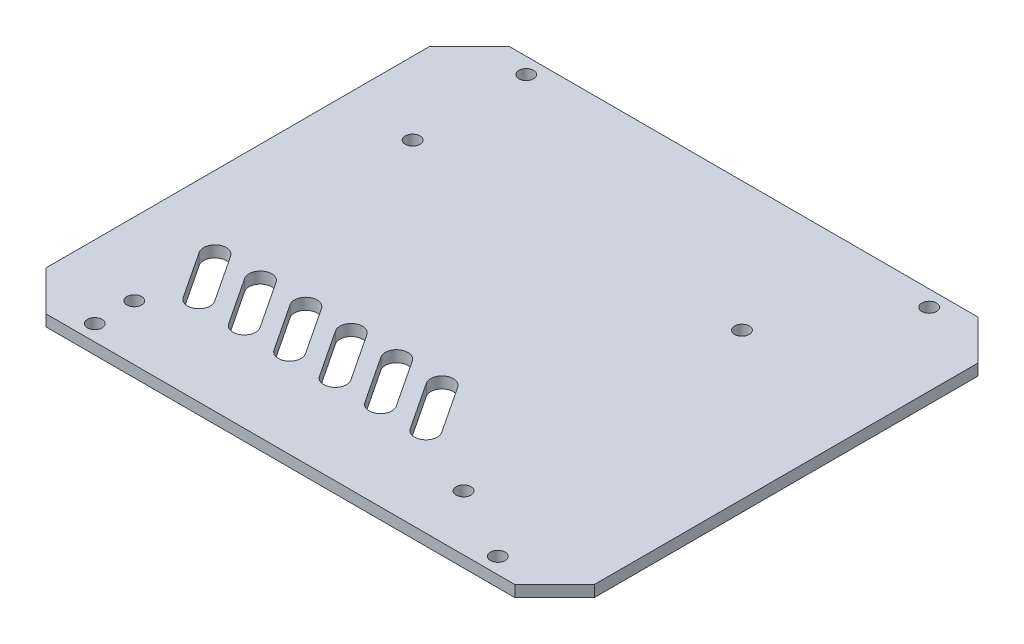
SolidWorks part; units mm, degrees
ref_plane "前视基准面" through (0, 0, 0) normal (0, 0, 1) x (1, 0, 0)
ref_plane "上视基准面" through (0, 0, 0) normal (0, 1, 0) x (1, 0, 0)
ref_plane "右视基准面" through (0, 0, 0) normal (1, 0, 0) x (0, 0, -1)
sketch "草图1" plane through (0, -19.39, 0) normal (0, -1, 0) x (1, 0, 0)
  line L16 (-51.8, -40.2958) -> (-44.7958, -47.3)
  line L17 (-44.7958, -47.3) -> (37.7958, -47.3)
  line L18 (37.7958, -47.3) -> (44.8, -40.2958)
  line L19 (44.8, -40.2958) -> (44.8, 27.2958)
  line L20 (44.8, 27.2958) -> (37.7958, 34.3)
  line L21 (-51.8, 27.2958) -> (-51.8, -40.2958)
  line L22 (37.7958, 34.3) -> (-44.7958, 34.3)
  line L23 (-44.7958, 34.3) -> (-51.8, 27.2958)
  line L24 (-51.8, -40.2958) -> (-44.7958, -47.3)
  line L25 (-44.7958, -47.3) -> (37.7958, -47.3)
  line L26 (37.7958, -47.3) -> (44.8, -40.2958)
  line L27 (44.8, -40.2958) -> (44.8, 27.2958)
  line L28 (44.8, 27.2958) -> (37.7958, 34.3)
  line L29 (-51.8, 27.2958) -> (-51.8, -40.2958)
  line L30 (37.7958, 34.3) -> (-44.7958, 34.3)
  line L31 (-44.7958, 34.3) -> (-51.8, 27.2958)
  dimension "D1" = 0.2
extrude "凸台-拉伸1" add sketch "草图1" along normal blind 2
sketch "草图2" plane through (0, -21.39, 0) normal (0, -1, 0) x (1, 0, 0)
  circle A0 centre (-39.0116, -24.5) radius 1.3
  circle A1 centre (19, -24.5) radius 1.3
  circle A2 centre (-39.0116, 24.5352) radius 1.3
  circle A3 centre (19, 24.5352) radius 1.3
  dimension "D1" = 2.6
extrude "切除-拉伸1" cut sketch "草图2" against normal up to next
sketch "草图3" plane through (0, -21.39, 0) normal (0, -1, 0) x (1, 0, 0)
  circle A0 centre (32, -44.5) radius 1.3 construction
  circle A1 centre (-39, -44.5) radius 1.3 construction
  circle A2 centre (32, 31.5) radius 1.3 construction
  circle A3 centre (-39, 31.5) radius 1.3 construction
  circle A4 centre (32, -44.5) radius 1.3
  circle A5 centre (-39, -44.5) radius 1.3
  circle A6 centre (32, 31.5) radius 1.3
  circle A7 centre (-39, 31.5) radius 1.3
extrude "切除-拉伸2" cut sketch "草图3" against normal up to next
sketch "草图4" plane through (0, -21.39, 0) normal (0, -1, 0) x (1, 0, 0)
  line L0 (-38.9928, 31.6194) -> (-39.0044, 24.6546) construction
  line L1 (-39.0282, 10.3) -> (-33.5143, 18.6425) construction
  line L2 (-40.6967, 11.4028) -> (-35.1828, 19.7453)
  line L3 (-37.3597, 9.1972) -> (-31.8458, 17.5397)
  line L5 (37.7958, 34.3) -> (-44.7958, 34.3) construction
  line L6 (-31.0282, 10.3) -> (-25.5143, 18.6425) construction
  line L9 (-32.6967, 11.4028) -> (-27.1828, 19.7453)
  line L12 (-29.3597, 9.1972) -> (-23.8458, 17.5397)
  line L15 (-23.0282, 10.3) -> (-17.5143, 18.6425) construction
  line L18 (-24.6967, 11.4028) -> (-19.1828, 19.7453)
  line L21 (-21.3597, 9.1972) -> (-15.8458, 17.5397)
  line L22 (-15.0282, 10.3) -> (-9.5143, 18.6425) construction
  line L23 (-16.6967, 11.4028) -> (-11.1828, 19.7453)
  line L24 (-13.3597, 9.1972) -> (-7.8458, 17.5397)
  line L25 (-7.0282, 10.3) -> (-1.5143, 18.6425) construction
  line L26 (-8.6967, 11.4028) -> (-3.1828, 19.7453)
  line L27 (-5.3597, 9.1972) -> (0.1542, 17.5397)
  line L28 (0.9718, 10.3) -> (6.4857, 18.6425) construction
  line L29 (-0.6967, 11.4028) -> (4.8172, 19.7453)
  line L30 (2.6403, 9.1972) -> (8.1542, 17.5397)
  arc A0 (-40.6967, 11.4028) -> (-37.3597, 9.1972) centre (-39.0282, 10.3) ccw
  arc A1 (-31.8458, 17.5397) -> (-35.1828, 19.7453) centre (-33.5143, 18.6425) ccw
  arc A12 (-32.6967, 11.4028) -> (-29.3597, 9.1972) centre (-31.0282, 10.3) ccw
  arc A13 (-23.8458, 17.5397) -> (-27.1828, 19.7453) centre (-25.5143, 18.6425) ccw
  arc A14 (-24.6967, 11.4028) -> (-21.3597, 9.1972) centre (-23.0282, 10.3) ccw
  arc A15 (-15.8458, 17.5397) -> (-19.1828, 19.7453) centre (-17.5143, 18.6425) ccw
  arc A16 (-16.6967, 11.4028) -> (-13.3597, 9.1972) centre (-15.0282, 10.3) ccw
  arc A17 (-7.8458, 17.5397) -> (-11.1828, 19.7453) centre (-9.5143, 18.6425) ccw
  arc A18 (-8.6967, 11.4028) -> (-5.3597, 9.1972) centre (-7.0282, 10.3) ccw
  arc A19 (0.1542, 17.5397) -> (-3.1828, 19.7453) centre (-1.5143, 18.6425) ccw
  arc A20 (-0.6967, 11.4028) -> (2.6403, 9.1972) centre (0.9718, 10.3) ccw
  arc A21 (8.1542, 17.5397) -> (4.8172, 19.7453) centre (6.4857, 18.6425) ccw
  point P6 (-36.2713, 14.4713)
  point P15 (-28.2713, 14.4713)
  point P22 (-20.2713, 14.4713)
  point P29 (-12.2713, 14.4713)
  point P36 (-4.2713, 14.4713)
  point P43 (3.7287, 14.4713)
  dimension "D1" = 2
  dimension "D2" = 10
  dimension "D3" = 5.5
  dimension "D4" = 12.8
  dimension "D5" = 24
  dimension "D6" = 6
extrude "切除-拉伸3" cut sketch "草图4" against normal up to next
sketch "草图5" plane through (0, -21.39, 0) normal (0, -1, 0) x (1, 0, 0)
  point P0 (-34.5006, 0.7543)
sketch_block_instance "块1-1"
sketch_block "块1"
sketch "草图6" plane through (0, -19.39, 0) normal (0, 1, 0) x (1, 0, 0)
  line L0 (-39.0322, 2.6968) -> (-34.8198, 0.2624) construction
  line L1 (-34.177, 0.2624) -> (-29.9873, 2.7014) construction
  line L2 (-29.9828, 3.2622) -> (-34.0539, 5.6966) construction
  line L3 (-29.6682, 9.5398) -> (-30.5435, 10.0367) construction
  line L4 (-30.6757, 9.9592) -> (-30.6757, 7.9487) construction
  line L5 (-30.6301, 7.8712) -> (-29.7548, 7.3788) construction
  line L6 (-29.6226, 7.4564) -> (-29.6226, 9.4623) construction
  line L7 (-33.3108, 9.1249) -> (-33.3108, 8.049) construction
  line L8 (-33.2652, 7.9715) -> (-32.8731, 7.7527) construction
  line L9 (-32.8458, 9.0109) -> (-33.2652, 9.2207) construction
  line L10 (-33.2652, 9.2207) -> (-33.2652, 10.0868) construction
  line L11 (-32.791, 9.8224) -> (-33.2652, 10.0868) construction
  line L12 (-34.3274, 7.7345) -> (-32.823, 6.8819) construction
  line L13 (-34.373, 12.0335) -> (-34.373, 7.8119) construction
  line L14 (-33.3563, 11.6095) -> (-34.2408, 12.111) construction
  line L15 (-33.3108, 10.1644) -> (-33.3108, 11.532) construction
  line L16 (-33.3108, 9.1249) -> (-33.3108, 10.1644) construction
  line L17 (-17.9609, 5.9474) -> (-18.6265, 5.6829) construction
  line L18 (-17.7011, 5.0538) -> (-17.0627, 4.2514) construction
  line L19 (-19.6477, 6.6221) -> (-18.9684, 6.9093) construction
  line L20 (-20.2085, 7.429) -> (-20.9333, 8.3134) construction
  line L21 (-10.1469, 9.1523) -> (-9.7593, 9.1523) construction
  line L22 (-5.5196, 7.1144) -> (-5.5196, 7.7664) construction
  line L23 (-26.0439, 6.3576) -> (-26.0439, 4.2651) construction
  line L24 (-26.0439, 4.2651) -> (-25.2871, 4.2651) construction
  line L25 (-25.2597, 6.3576) -> (-26.0439, 6.3576) construction
  line L26 (-26.7095, 3.7272) -> (-26.7095, 8.979) construction
  line L27 (-26.7095, 8.979) -> (-26.0439, 8.979) construction
  line L28 (-26.0439, 8.979) -> (-26.0439, 6.8956) construction
  line L29 (-26.0439, 6.8956) -> (-25.1731, 6.8956) construction
  line L30 (-25.2096, 3.7272) -> (-26.7095, 3.7272) construction
  line L31 (-33.1558, -0.189) -> (-33.8122, -0.5719) construction
  line L32 (-35.189, -0.5719) -> (-35.8455, -0.189) construction
  line L33 (-35.8455, -0.189) -> (-39.2511, 1.7759) construction
  line L34 (-39.2511, 1.7759) -> (-39.9076, 2.1543) construction
  line L35 (-40.596, 3.3442) -> (-40.596, 8.7967) construction
  line L36 (-39.9076, 9.9866) -> (-39.2511, 10.365) construction
  line L37 (-39.2511, 10.365) -> (-35.8455, 12.3299) construction
  line L38 (-35.8455, 12.3299) -> (-35.189, 12.7128) construction
  line L39 (-33.8122, 12.7128) -> (-33.1558, 12.3299) construction
  line L40 (-33.1558, 12.3299) -> (-29.7503, 10.365) construction
  line L41 (-29.7503, 10.365) -> (-29.0938, 9.9866) construction
  line L42 (-28.4054, 8.7967) -> (-28.4054, 3.3442) construction
  line L43 (-29.0938, 2.1543) -> (-29.7503, 1.7759) construction
  line L44 (-29.7503, 1.7759) -> (-33.1558, -0.189) construction
  line L45 (-5.3737, 8.5687) -> (-5.2826, 8.979) construction
  line L46 (-5.2826, 8.979) -> (-4.2431, 8.979) construction
  line L47 (-4.2431, 8.979) -> (-4.2431, 6.6631) construction
  line L48 (-7.6486, 5.3365) -> (-7.2018, 6.1753) construction
  line L49 (-5.4056, 8.5687) -> (-5.3737, 8.5687) construction
  line L50 (-8.0133, 5.8243) -> (-8.0133, 4.9034) construction
  line L51 (-8.0133, 4.9034) -> (-9.5086, 4.9034) construction
  line L52 (-11.3094, 7.3378) -> (-11.3094, 7.3652) construction
  line L53 (-11.3869, 8.8286) -> (-11.3869, 8.8651) construction
  line L54 (-9.5178, 8.1767) -> (-10.1606, 8.1767) construction
  line L55 (-8.6424, 5.8243) -> (-8.0133, 5.8243) construction
  line L56 (-13.8761, 4.9034) -> (-13.8761, 7.5749) construction
  line L57 (-15.0295, 7.2649) -> (-15.0295, 4.9034) construction
  line L58 (-15.0295, 4.9034) -> (-16.3014, 4.9034) construction
  line L59 (-16.3014, 4.9034) -> (-16.3014, 7.4245) construction
  line L60 (-13.7575, 8.4183) -> (-13.7302, 8.4183) construction
  line L61 (-13.7302, 8.4183) -> (-13.639, 8.979) construction
  line L62 (-13.639, 8.979) -> (-12.5996, 8.979) construction
  line L63 (-12.5996, 8.979) -> (-12.5996, 4.9034) construction
  line L64 (-12.5996, 4.9034) -> (-13.8761, 4.9034) construction
  line L65 (-21.7265, 8.979) -> (-21.7265, 5.0857) construction
  line L66 (-22.3785, 8.979) -> (-21.7265, 8.979) construction
  line L67 (-22.3785, 5.0857) -> (-22.3785, 8.979) construction
  line L68 (-21.7265, 5.0857) -> (-22.3785, 5.0857) construction
  line L69 (-3.4042, 8.979) -> (-2.1368, 8.979) construction
  line L70 (-2.1368, 8.979) -> (-2.1368, 6.6494) construction
  line L71 (-0.8102, 5.9838) -> (-0.596, 4.8851) construction
  line L72 (-2.2508, 5.61) -> (-2.2782, 5.61) construction
  line L73 (-2.2782, 5.61) -> (-2.3648, 4.9034) construction
  line L74 (-2.3648, 4.9034) -> (-3.4042, 4.9034) construction
  line L75 (-3.4042, 4.9034) -> (-3.4042, 8.979) construction
  line L76 (-39.0322, 2.6968) -> (-34.8198, 0.2624)
  line L77 (-34.177, 0.2624) -> (-29.9873, 2.7014)
  line L78 (-29.9828, 3.2622) -> (-34.0539, 5.6966)
  line L79 (-29.6682, 9.5398) -> (-30.5435, 10.0367)
  line L80 (-30.6757, 9.9592) -> (-30.6757, 7.9487)
  line L81 (-30.6301, 7.8712) -> (-29.7548, 7.3788)
  line L82 (-29.6226, 7.4564) -> (-29.6226, 9.4623)
  line L83 (-33.3108, 9.1249) -> (-33.3108, 8.049)
  line L84 (-33.2652, 7.9715) -> (-32.8731, 7.7527)
  line L85 (-32.8458, 9.0109) -> (-33.2652, 9.2207)
  line L86 (-33.2652, 9.2207) -> (-33.2652, 10.0868)
  line L87 (-32.791, 9.8224) -> (-33.2652, 10.0868)
  line L88 (-34.3274, 7.7345) -> (-32.823, 6.8819)
  line L89 (-34.373, 12.0335) -> (-34.373, 7.8119)
  line L90 (-33.3563, 11.6095) -> (-34.2408, 12.111)
  line L91 (-33.3108, 10.1644) -> (-33.3108, 11.532)
  line L92 (-33.3108, 9.1249) -> (-33.3108, 10.1644)
  line L93 (-17.9609, 5.9474) -> (-18.6265, 5.6829)
  line L94 (-17.7011, 5.0538) -> (-17.0627, 4.2514)
  line L95 (-19.6477, 6.6221) -> (-18.9684, 6.9093)
  line L96 (-20.2085, 7.429) -> (-20.9333, 8.3134)
  line L97 (-10.1469, 9.1523) -> (-9.7593, 9.1523)
  line L98 (-5.5196, 7.1144) -> (-5.5196, 7.7664)
  line L99 (-26.0439, 6.3576) -> (-26.0439, 4.2651)
  line L100 (-26.0439, 4.2651) -> (-25.2871, 4.2651)
  line L101 (-25.2597, 6.3576) -> (-26.0439, 6.3576)
  line L102 (-26.7095, 3.7272) -> (-26.7095, 8.979)
  line L103 (-26.7095, 8.979) -> (-26.0439, 8.979)
  line L104 (-26.0439, 8.979) -> (-26.0439, 6.8956)
  line L105 (-26.0439, 6.8956) -> (-25.1731, 6.8956)
  line L106 (-25.2096, 3.7272) -> (-26.7095, 3.7272)
  line L107 (-33.1558, -0.189) -> (-33.8122, -0.5719)
  line L108 (-35.189, -0.5719) -> (-35.8455, -0.189)
  line L109 (-35.8455, -0.189) -> (-39.2511, 1.7759)
  line L110 (-39.2511, 1.7759) -> (-39.9076, 2.1543)
  line L111 (-40.596, 3.3442) -> (-40.596, 8.7967)
  line L112 (-39.9076, 9.9866) -> (-39.2511, 10.365)
  line L113 (-39.2511, 10.365) -> (-35.8455, 12.3299)
  line L114 (-35.8455, 12.3299) -> (-35.189, 12.7128)
  line L115 (-33.8122, 12.7128) -> (-33.1558, 12.3299)
  line L116 (-33.1558, 12.3299) -> (-29.7503, 10.365)
  line L117 (-29.7503, 10.365) -> (-29.0938, 9.9866)
  line L118 (-28.4054, 8.7967) -> (-28.4054, 3.3442)
  line L119 (-29.0938, 2.1543) -> (-29.7503, 1.7759)
  line L120 (-29.7503, 1.7759) -> (-33.1558, -0.189)
  line L121 (-5.3737, 8.5687) -> (-5.2826, 8.979)
  line L122 (-5.2826, 8.979) -> (-4.2431, 8.979)
  line L123 (-4.2431, 8.979) -> (-4.2431, 6.6631)
  line L124 (-7.6486, 5.3365) -> (-7.2018, 6.1753)
  line L125 (-5.4056, 8.5687) -> (-5.3737, 8.5687)
  line L126 (-8.0133, 5.8243) -> (-8.0133, 4.9034)
  line L127 (-8.0133, 4.9034) -> (-9.5086, 4.9034)
  line L128 (-11.3094, 7.3378) -> (-11.3094, 7.3652)
  line L129 (-11.3869, 8.8286) -> (-11.3869, 8.8651)
  line L130 (-9.5178, 8.1767) -> (-10.1606, 8.1767)
  line L131 (-8.6424, 5.8243) -> (-8.0133, 5.8243)
  line L132 (-13.8761, 4.9034) -> (-13.8761, 7.5749)
  line L133 (-15.0295, 7.2649) -> (-15.0295, 4.9034)
  line L134 (-15.0295, 4.9034) -> (-16.3014, 4.9034)
  line L135 (-16.3014, 4.9034) -> (-16.3014, 7.4245)
  line L136 (-13.7575, 8.4183) -> (-13.7302, 8.4183)
  line L137 (-13.7302, 8.4183) -> (-13.639, 8.979)
  line L138 (-13.639, 8.979) -> (-12.5996, 8.979)
  line L139 (-12.5996, 8.979) -> (-12.5996, 4.9034)
  line L140 (-12.5996, 4.9034) -> (-13.8761, 4.9034)
  line L141 (-21.7265, 8.979) -> (-21.7265, 5.0857)
  line L142 (-22.3785, 8.979) -> (-21.7265, 8.979)
  line L143 (-22.3785, 5.0857) -> (-22.3785, 8.979)
  line L144 (-21.7265, 5.0857) -> (-22.3785, 5.0857)
  line L145 (-3.4042, 8.979) -> (-2.1368, 8.979)
  line L146 (-2.1368, 8.979) -> (-2.1368, 6.6494)
  line L147 (-0.8102, 5.9838) -> (-0.596, 4.8851)
  line L148 (-2.2508, 5.61) -> (-2.2782, 5.61)
  line L149 (-2.2782, 5.61) -> (-2.3648, 4.9034)
  line L150 (-2.3648, 4.9034) -> (-3.4042, 4.9034)
  line L151 (-3.4042, 4.9034) -> (-3.4042, 8.979)
  spline S0 degree 3 poles (1947.2043, 259.0221) (-2040.5975, -86.3945) (1971.5647, -86.1046) (-2015.9835, 259.8919) knots -24.014283 -24.014283 -24.014283 -24.014283 31.060476 31.060476 31.060476 31.060476 only from (-34.8198, 0.2624) to (-34.177, 0.2624) construction
  spline S1 degree 3 poles (-178.8618, 1996.4067) (-13.3017, -2002.4803) (85.7628, 2005.1657) (-277.1173, -1980.6649) knots -12.069605 -12.069605 -12.069605 -12.069605 23.053377 23.053377 23.053377 23.053377 only from (-29.9873, 2.7014) to (-29.9828, 3.2622) construction
  spline S2 degree 3 poles (-2011.9647, -280.5218) (1973.0796, 101.2598) (-2042.0834, 101.2623) (1942.99, -280.5143) knots -16.956312 -16.956312 -16.956312 -16.956312 31.955994 31.955994 31.955994 31.955994 only from (-34.0539, 5.6966) to (-34.9429, 5.6966) construction
  spline S3 degree 2 poles (1696.8938, 1005.9909) (-1772.9636, -998.1959) (1692.7429, 1003.6514) knots -19.544322 -19.544322 -19.544322 21.524182 21.524182 21.524182 only from (-34.9429, 5.6966) to (-39.0732, 3.3123) construction
  spline S4 degree 3 poles (312.9236, -1964.6822) (-255.5836, 1997.2947) (39.8207, -2001.4292) (20.6091, 2000.9771) knots -16.033039 -16.033039 -16.033039 -16.033039 19.060221 19.060221 19.060221 19.060221 only from (-39.0732, 3.3123) to (-39.0322, 2.6968) construction
  spline S5 degree 3 poles (1612.1466, 1139.1382) (-173.749, 124.6775) (-29.5451, -1.4055) (-29.5451, 6.2482) (-29.5451, 12.5795) (-131.1047, 41.0713) (891.7703, -1766.7786) knots -20.983072 -20.983072 -20.983072 -20.983072 3 3 3 23.1269 23.1269 23.1269 23.1269 only from (-30.1469, 6.0431) to (-30.1469, 7.1281) construction
  spline S6 degree 3 poles (-1593.6748, -1232.4433) (112.4759, -108.2288) (-30.7532, 14.45) (-30.7532, 6.9321) (-30.7532, 0.2328) (76.6581, -24.0346) (-1002.5668, 1752.6044) knots -22.899222 -22.899222 -22.899222 -22.899222 1 1 1 21.696321 21.696321 21.696321 21.696321 only from (-30.1469, 7.1281) to (-30.1469, 6.0431) construction
  spline S7 degree 3 poles (-1735.267, -1035.1971) (1720.3132, 981.2712) (-1822.079, -884.2768) (1795.5461, 824.5182) knots -24.864003 -24.864003 -24.864003 -24.864003 29.805716 29.805716 29.805716 29.805716 only from (-30.5435, 10.0367) to (-30.6757, 9.9592) construction
  spline S8 degree 3 poles (1803.8452, -787.8206) (-1835.1338, 879.7734) (1736.3613, -937.8925) (-1752.2845, 1025.0132) knots -52.644856 -52.644856 -52.644856 -52.644856 63.422153 63.422153 63.422153 63.422153 only from (-30.6757, 7.9487) to (-30.6301, 7.8712) construction
  spline S9 degree 3 poles (1675.9971, 1050.9308) (-1781.5786, -962.103) (1762.6814, 899.8753) (-1856.6746, -805.2277) knots -20.869425 -20.869425 -20.869425 -20.869425 33.809897 33.809897 33.809897 33.809897 only from (-29.7548, 7.3788) to (-29.6226, 7.4564) construction
  spline S10 degree 3 poles (-1017.153, 1748.416) (898.1967, -1765.8691) (-895.3334, 1815.971) (771.5167, -1822.726) knots -45.73326 -45.73326 -45.73326 -45.73326 46.535072 46.535072 46.535072 46.535072 only from (-29.6226, 9.4623) to (-29.6682, 9.5398) construction
  spline S11 degree 3 poles (1241.4728, -1544.2848) (-126.4363, -19.7603) (-21.5989, 9.5171) (-21.5989, 3.8639) (-21.5989, -3.1211) (-150.7291, 66.7677) (1747.5616, 931.244) knots -20.398043 -20.398043 -20.398043 -20.398043 3 3 3 28.967808 28.967808 28.967808 28.967808 only from (-22.0502, 4.2833) to (-22.0502, 3.44) construction
  spline S12 degree 3 poles (-1791.638, 931.233) (106.6275, 66.7672) (-22.5016, -3.1211) (-22.5016, 3.8639) (-22.5016, 9.5171) (82.3355, -19.7602) (-1285.567, -1544.2778) knots -24.967698 -24.967698 -24.967698 -24.967698 1 1 1 24.398007 24.398007 24.398007 24.398007 only from (-22.0502, 3.44) to (-22.0502, 4.2833) construction
  spline S13 degree 3 poles (953.112, -1731.5311) (-960.0271, 1783.9495) (831.3079, -1798.9714) (-833.3757, 1840.6921) knots -41.715469 -41.715469 -41.715469 -41.715469 50.515238 50.515238 50.515238 50.515238 only from (-33.3108, 8.049) to (-33.2652, 7.9715) construction
  spline S14 degree 3 poles (345.3515, -1953.7628) (-656.074, 2008.4671) (704.4049, -1945.0024) (-795.7723, 1856.1671) knots -18.836401 -18.836401 -18.836401 -18.836401 26.867419 26.867419 26.867419 26.867419 only from (-32.8731, 7.7527) to (-32.0799, 7.9031) construction
  spline S15 degree 3 poles (393.8329, 1947.428) (-1017.3565, -1766.8215) (1294.138, 1559.3727) (-1541.9229, -1298.5467) knots -37.738435 -37.738435 -37.738435 -37.738435 30.849118 30.849118 30.849118 30.849118 only from (-32.0799, 7.9031) to (-32.8458, 9.0109) construction
  spline S16 degree 3 poles (-1970.6267, 490.4514) (1900.3877, -652.3893) (-1909.3139, 822.203) (1735.9268, -921.8099) knots -2.984455 -2.984455 -2.984455 -2.984455 24.908291 24.908291 24.908291 24.908291 only from (-31.0405, 7.315) to (-32.791, 9.8224) construction
  spline S17 degree 3 poles (1301.0551, -1483.1694) (-1380.7778, 1570.3517) (1272.9624, -1585.6466) (-1251.2088, 1591.7607) knots -4.177868 -4.177868 -4.177868 -4.177868 21.267464 21.267464 21.267464 21.267464 only from (-32.823, 6.8819) to (-31.0405, 7.315) construction
  spline S18 degree 3 poles (-426.7908, -1953.0944) (416.9018, 1960.3516) (-543.6183, -1930.3492) (531.9657, 1925.7159) knots -40.574336 -40.574336 -40.574336 -40.574336 54.224541 54.224541 54.224541 54.224541 only from (-34.373, 7.8119) to (-34.3274, 7.7345) construction
  spline S19 degree 3 poles (-1739.7201, -1031.8845) (1717.3311, 982.0362) (-1826.4475, -880.8273) (1792.473, 825.1567) knots -21.867988 -21.867988 -21.867988 -21.867988 32.80886 32.80886 32.80886 32.80886 only from (-34.2408, 12.111) to (-34.373, 12.0335) construction
  spline S20 degree 3 poles (1326.5597, 1477.8337) (-1443.7748, -1422.5109) (1417.5131, 1403.8248) (-1515.2659, -1331.1895) knots -66.611259 -66.611259 -66.611259 -66.611259 68.63044 68.63044 68.63044 68.63044 only from (-33.3108, 11.532) to (-33.3563, 11.6095) construction
  spline S21 degree 3 poles (-1127.9465, 1668.9065) (1205.0665, -1581.8003) (-1320.6139, 1532.1331) (1326.4072, -1474.1074) knots -17.356672 -17.356672 -17.356672 -17.356672 19.212167 19.212167 19.212167 19.212167 only from (-18.6265, 5.6829) to (-19.4334, 5.0857) construction
  spline S22 degree 3 poles (1945.6237, -352.8331) (-1917.2958, 619.5498) (1753.4488, -897.6325) (-1594.6226, 1226.9154) knots -23.773694 -23.773694 -23.773694 -23.773694 31.399142 31.399142 31.399142 31.399142 only from (-19.4334, 5.0857) to (-18.7952, 4.6435) construction
  spline S23 degree 3 poles (-1957.8604, 491.3787) (1905.2875, -332.0334) (-1960.1859, 166.6666) (1980.2936, 44.6676) knots -22.175827 -22.175827 -22.175827 -22.175827 30.019969 30.019969 30.019969 30.019969 only from (-18.7952, 4.6435) to (-17.7011, 5.0538) construction
  spline S24 degree 3 poles (-1996.9289, 274.3391) (2008.3741, -55.5657) (-2041.9478, -141.8187) (1949.9756, 346.3582) knots -14.985955 -14.985955 -14.985955 -14.985955 26.624596 26.624596 26.624596 26.624596 only from (-17.0627, 4.2514) to (-18.7952, 3.5448) construction
  spline S25 degree 3 poles (-959.5674, 1764.5293) (1176.2874, -1603.5878) (-1432.6495, 1427.6748) (1567.7803, -1205.173) knots -7.558703 -7.558703 -7.558703 -7.558703 20.482777 20.482777 20.482777 20.482777 only from (-18.7952, 3.5448) to (-20.7327, 5.1587) construction
  spline S26 degree 3 poles (1924.0493, -458.54) (-2016.5165, 343.495) (1995.4741, -211.501) (-2016.1303, 116.1959) knots -7.852621 -7.852621 -7.852621 -7.852621 24.144848 24.144848 24.144848 24.144848 only from (-20.7327, 5.1587) to (-19.6477, 6.6221) construction
  spline S27 degree 3 poles (615.0637, -1888.8545) (-795.6899, 1841.0297) (868.9978, -1778.6578) (-986.0957, 1757.28) knots -9.138526 -9.138526 -9.138526 -9.138526 27.25787 27.25787 27.25787 27.25787 only from (-18.9684, 6.9093) to (-18.2162, 7.5111) construction
  spline S28 degree 3 poles (215.7009, 1986.9997) (-654.6592, -1923.8751) (894.6606, 1828.6602) (-1110.216, -1665.8008) knots -22.542702 -22.542702 -22.542702 -22.542702 37.658646 37.658646 37.658646 37.658646 only from (-18.2162, 7.5111) to (-18.9137, 7.9761) construction
  spline S29 degree 3 poles (-1605.429, -1208.7716) (1666.7814, 1140.7416) (-1773.5402, -1019.3674) (1765.9801, 905.5471) knots -8.791084 -8.791084 -8.791084 -8.791084 32.386114 32.386114 32.386114 32.386114 only from (-18.9137, 7.9761) to (-20.2085, 7.429) construction
  spline S30 degree 3 poles (1966.5787, -197.5818) (-2051.7497, -0.967) (2002.48, 224.4874) (-1974.8286, -400.794) knots -6.294928 -6.294928 -6.294928 -6.294928 33.756853 33.756853 33.756853 33.756853 only from (-20.9333, 8.3134) to (-18.9411, 9.0793) construction
  spline S31 degree 3 poles (124.1341, -1982.3989) (-457.1442, 1958.1164) (708.8959, -1855.2284) (-1015.0804, 1736.3895) knots 0.697384 0.697384 0.697384 0.697384 28.978211 28.978211 28.978211 28.978211 only from (-18.9411, 9.0793) to (-16.9033, 7.4108) construction
  spline S32 degree 3 poles (-1495.2544, 1354.2838) (1523.5493, -1377.9736) (-1538.1686, 1424.3054) (1353.4505, -1448.6746) knots -4.734801 -4.734801 -4.734801 -4.734801 40.265101 40.265101 40.265101 40.265101 only from (-16.9033, 7.4108) to (-17.9609, 5.9474) construction
  spline S33 degree 3 poles (-1961.8056, -418.0731) (126.6492, -101.6131) (-10.6711, 16.7967) (-10.6711, 6.2847) (-10.6711, -3.9538) (125.3735, 107.9903) (-1932.7785, 547.0377) knots -21.79377 -21.79377 -21.79377 -21.79377 3 3 3 27.67833 27.67833 27.67833 27.67833 only from (-10.156, 6.923) to (-10.156, 5.6556) construction
  spline S34 degree 3 poles (1882.1607, 641.7029) (-158.572, 123.862) (-9.6409, -4.6535) (-9.6409, 6.2847) (-9.6409, 17.5385) (-160.5965, -118.9677) (1923.9331, -488.0552) knots -25.364902 -25.364902 -25.364902 -25.364902 1 1 1 27.543492 27.543492 27.543492 27.543492 only from (-10.156, 5.6556) to (-10.156, 6.923) construction
  spline S35 degree 3 poles (398.3769, -1946.8651) (-621.0655, 1916.7975) (746.5301, -1849.6014) (-860.4662, 1818.6943) knots -20.367991 -20.367991 -20.367991 -20.367991 27.043685 27.043685 27.043685 27.043685 only from (-9.7593, 9.1523) to (-9.1667, 9.4441) construction
  spline S36 degree 3 poles (-1851.6901, 784.2948) (1770.8918, -932.7585) (-1685.1957, 1125.6418) (1512.1872, -1283.8884) knots -14.155704 -14.155704 -14.155704 -14.155704 26.455766 26.455766 26.455766 26.455766 only from (-9.1667, 9.4441) to (-10.0557, 9.8954) construction
  spline S37 degree 3 poles (-1999.7746, -177.9397) (2048.5506, 17.7992) (-2059.7856, 149.4036) (1971.6374, -249.0633) knots -24.53604 -24.53604 -24.53604 -24.53604 22.203045 22.203045 22.203045 22.203045 only from (-10.0557, 9.8954) to (-10.9219, 9.4668) construction
  spline S38 degree 3 poles (335.4233, 1977.3974) (-130.5762, -1935.4278) (-138.8194, 1950.0115) (386.7962, -1948.2187) knots -42.090152 -42.090152 -42.090152 -42.090152 46.007634 46.007634 46.007634 46.007634 only from (-10.9219, 9.4668) to (-10.7304, 9.1021) construction
  spline S39 degree 3 poles (-2000.164, -195.6542) (1968.231, 177.2652) (-1992.5781, -127.132) (1986.8184, 117.9013) knots -23.761314 -23.761314 -23.761314 -23.761314 27.411452 27.411452 27.411452 27.411452 only from (-10.7304, 9.1021) to (-10.1469, 9.1523) construction
  spline S40 degree 3 poles (1900.4815, 611.268) (-1853.5024, -713.4995) (1804.2956, 824.4669) (-1796.5625, -882.5407) knots -25.691977 -25.691977 -25.691977 -25.691977 25.491412 25.491412 25.491412 25.491412 only from (-5.5196, 7.7664) to (-6.135, 8.09) construction
  spline S41 degree 3 poles (-2003.4629, -52.8338) (2017.9029, -136.2777) (-2009.5197, 324.3726) (1939.2706, -450.8338) knots -29.27083 -29.27083 -29.27083 -29.27083 28.779665 28.779665 28.779665 28.779665 only from (-6.135, 8.09) to (-6.5727, 7.739) construction
  spline S42 degree 3 poles (-1965.4656, -395.4958) (1971.7383, 441.6954) (-1983.3474, -426.4496) (1951.4791, 419.1184) knots -18.272249 -18.272249 -18.272249 -18.272249 20.366917 20.366917 20.366917 20.366917 only from (-6.5727, 7.739) to (-5.5196, 7.1144) construction
  spline S43 degree 3 poles (-552.3477, -1916.0072) (39.6444, 1949.1893) (231.1798, -1947.9287) (-488.2476, 1949.0672) knots -16.951569 -16.951569 -16.951569 -16.951569 21.292276 21.292276 21.292276 21.292276 only from (-25.2871, 4.2651) to (-23.9011, 5.2681) construction
  spline S44 degree 3 poles (74.9674, -1978.7796) (-669.1868, 1491.4113) (1220.9961, -1007.5518) (-1925.4997, 576.7533) knots -20.703775 -20.703775 -20.703775 -20.703775 29.911591 29.911591 29.911591 29.911591 only from (-23.9011, 5.2681) to (-25.2597, 6.3576) construction
  spline S45 degree 3 poles (1967.7044, -102.3152) (-2083.6001, -202.2982) (1987.7708, 465.393) (-1913.3422, -643.1952) knots -12.662635 -12.662635 -12.662635 -12.662635 20.708978 20.708978 20.708978 20.708978 only from (-25.1731, 6.8956) to (-23.2401, 5.2681) construction
  spline S46 degree 3 poles (-1462.7137, 1393.5071) (1511.2501, -1404.3078) (-1580.4996, 1407.0991) (1432.7296, -1365.1759) knots -7.615095 -7.615095 -7.615095 -7.615095 23.693651 23.693651 23.693651 23.693651 only from (-23.2401, 5.2681) to (-25.2096, 3.7272) construction
  spline S47 degree 3 poles (-1986.2159, -424.6605) (1872.5149, 650.7296) (-1856.7008, -859.0204) (1668.1443, 1044.8861) knots -40.403395 -40.403395 -40.403395 -40.403395 46.454358 46.454358 46.454358 46.454358 only from (-33.8122, -0.5719) to (-34.5006, -0.7543) construction
  spline S48 degree 3 poles (-1740.3489, 1039.5921) (1790.0962, -854.0172) (-1943.0897, 646.2372) (1918.0006, -420.927) knots -38.373718 -38.373718 -38.373718 -38.373718 48.302597 48.302597 48.302597 48.302597 only from (-34.5006, -0.7543) to (-35.189, -0.5719) construction
  spline S49 degree 3 poles (-754.8971, 1867.8409) (885.9932, -1784.6) (-1157.7277, 1677.1962) (1246.9181, -1524.5355) knots -12.834285 -12.834285 -12.834285 -12.834285 29.798641 29.798641 29.798641 29.798641 only from (-39.9076, 2.1543) to (-40.596, 3.3442) construction
  spline S50 degree 3 poles (1310.7611, 1480.2732) (-1219.4015, -1620.1293) (943.9093, 1763.7167) (-807.2491, -1834.6442) knots -11.169927 -11.169927 -11.169927 -11.169927 32.277267 32.277267 32.277267 32.277267 only from (-40.596, 8.7967) to (-39.9076, 9.9866) construction
  spline S51 degree 3 poles (1829.5545, -704.5958) (-1983.3127, 518.655) (1959.6502, -271.0062) (-2031.7382, 64.4568) knots -28.630568 -28.630568 -28.630568 -28.630568 59.634843 59.634843 59.634843 59.634843 only from (-35.189, 12.7128) to (-34.5006, 12.8952) construction
  spline S52 degree 3 poles (1962.7022, 65.7414) (-2028.2181, -273.3756) (1913.3784, 521.8911) (-1897.0742, -708.4939) knots -29.74703 -29.74703 -29.74703 -29.74703 58.724161 58.724161 58.724161 58.724161 only from (-34.5006, 12.8952) to (-33.8122, 12.7128) construction
  spline S53 degree 3 poles (611.3262, -1882.3455) (-897.4898, 1821.8566) (1049.2417, -1687.0258) (-1295.1838, 1553.5314) knots -2.467628 -2.467628 -2.467628 -2.467628 41.506639 41.506639 41.506639 41.506639 only from (-29.0938, 9.9866) to (-28.4054, 8.7967) construction
  spline S54 degree 3 poles (-1230.5684, -1592.4268) (988.9215, 1738.3623) (-842.904, -1836.9675) (564.0724, 1910.0048) knots -0.095652 -0.095652 -0.095652 -0.095652 42.997123 42.997123 42.997123 42.997123 only from (-28.4054, 3.3442) to (-29.0938, 2.1543) construction
  spline S55 degree 3 poles (-1430.5573, 1407.5659) (1723.1127, -1481.9909) (-1919.6145, 1389.7982) (1763.4855, -917.7581) knots -7.107453 -7.107453 -7.107453 -7.107453 39.300169 39.300169 39.300169 39.300169 only from (-4.2431, 6.6631) to (-5.8934, 4.8031) construction
  spline S56 degree 3 poles (200.3126, 1993.6618) (-113.4143, -2029.6162) (37.9701, 2047.0917) (-46.8978, -1994.2146) knots -24.475698 -24.475698 -24.475698 -24.475698 28.452112 28.452112 28.452112 28.452112 only from (-5.8934, 4.8031) to (-7.6486, 5.3365) construction
  spline S57 degree 3 poles (-1933.6669, -520.0604) (1769.2026, 770.3694) (-1678.914, -975.8177) (1607.9896, 1184.3814) knots -29.345565 -29.345565 -29.345565 -29.345565 33.949512 33.949512 33.949512 33.949512 only from (-7.2018, 6.1753) to (-6.135, 5.8197) construction
  spline S58 degree 3 poles (-1709.7987, 1053.3931) (1749.403, -1046.8479) (-1793.7464, 1008.7473) (1793.1121, -866.6254) knots -20.675466 -20.675466 -20.675466 -20.675466 32.208493 32.208493 32.208493 32.208493 only from (-6.135, 5.8197) to (-5.5196, 6.3394) construction
  spline S59 degree 3 poles (1975.7527, -248.8039) (-1868.9813, 512.6632) (1631.6647, -894.331) (-1295.7423, 1512.4535) knots -12.733532 -12.733532 -12.733532 -12.733532 25.757539 25.757539 25.757539 25.757539 only from (-5.5196, 6.3394) to (-7.7854, 7.8393) construction
  spline S60 degree 3 poles (1042.4421, 1706.8309) (-834.6219, -1820.7719) (589.0356, 1925.2458) (-367.8223, -1955.7065) knots -11.03402 -11.03402 -11.03402 -11.03402 21.264003 21.264003 21.264003 21.264003 only from (-7.7854, 7.8393) to (-6.5727, 9.0793) construction
  spline S61 degree 3 poles (-582.1125, -1906.1013) (523.4678, 1965.3983) (-513.1262, -1956.0805) (513.8823, 1939.9285) knots -17.627726 -17.627726 -17.627726 -17.627726 33.245267 33.245267 33.245267 33.245267 only from (-6.5727, 9.0793) to (-5.4056, 8.5687) construction
  spline S62 degree 3 poles (-1930.5691, 559.3395) (1974.8488, -448.3348) (-2018.9786, 347.7304) (1976.7281, -218.5664) knots -33.500705 -33.500705 -33.500705 -33.500705 55.20773 55.20773 55.20773 55.20773 only from (-9.5086, 4.9034) to (-10.156, 4.8031) construction
  spline S63 degree 3 poles (-1999.2913, 198.6019) (2020.2524, -1.5641) (-2032.1384, -171.0059) (1955.7763, 357.6437) knots -3.872904 -3.872904 -3.872904 -3.872904 23.676976 23.676976 23.676976 23.676976 only from (-10.156, 4.8031) to (-11.8611, 6.2847) construction
  spline S64 degree 3 poles (1939.5115, 440.407) (-1940.4923, -577.4399) (1873.7743, 723.7895) (-1830.7521, -821.4821) knots -8.023341 -8.023341 -8.023341 -8.023341 31.752387 31.752387 31.752387 31.752387 only from (-11.8611, 6.2847) to (-11.3094, 7.3378) construction
  spline S65 degree 3 poles (-1329.9726, 1509.8665) (1428.2205, -1408.3534) (-1547.8279, 1317.3332) (1597.8765, -1177.5524) knots -10.762319 -10.762319 -10.762319 -10.762319 36.904963 36.904963 36.904963 36.904963 only from (-11.3094, 7.3652) to (-11.7608, 8.1265) construction
  spline S66 degree 3 poles (1690.5146, -1041.4074) (-1758.3489, 1014.3497) (1757.9984, -959.3158) (-1776.7351, 948.7003) knots -9.879735 -9.879735 -9.879735 -9.879735 41.23424 41.23424 41.23424 41.23424 only from (-11.7608, 8.1265) to (-11.3869, 8.8286) construction
  spline S67 degree 3 poles (-752.9374, 1842.3255) (1308.8718, -1353.5914) (-1702.759, 958.5145) (1892.0914, -582.47) knots -26.637538 -26.637538 -26.637538 -26.637538 53.487657 53.487657 53.487657 53.487657 only from (-11.3869, 8.8651) to (-11.9659, 9.6674) construction
  spline S68 degree 3 poles (1894.089, -594.3405) (-1996.6922, 519.1508) (2004.2706, -389.5025) (-1990.0486, 289.9866) knots 3.488718 3.488718 3.488718 3.488718 33.266204 33.266204 33.266204 33.266204 only from (-11.9659, 9.6674) to (-10.2563, 10.6932) construction
  spline S69 degree 3 poles (883.5316, -1769.7092) (-1265.933, 1528.3806) (1531.048, -1233.7757) (-1756.2499, 971.1381) knots 2.502912 2.502912 2.502912 2.502912 33.788332 33.788332 33.788332 33.788332 only from (-10.2563, 10.6932) to (-7.9495, 9.2207) construction
  spline S70 degree 3 poles (-1471.0119, 1372.7307) (1578.4938, -1482.6464) (-1566.0618, 1580.68) (1222.054, -1564.0225) knots 0.121158 0.121158 0.121158 0.121158 45.755216 45.755216 45.755216 45.755216 only from (-7.9495, 9.2207) to (-9.5178, 8.1767) construction
  spline S71 degree 3 poles (1988.9699, 46.517) (-2010.5704, -146.5098) (1966.0388, 323.2501) (-1936.5111, -524.1006) knots -22.92357 -22.92357 -22.92357 -22.92357 29.602258 29.602258 29.602258 29.602258 only from (-10.1606, 8.1767) to (-10.7623, 7.9031) construction
  spline S72 degree 3 poles (-533.5031, 1938.1422) (580.6394, -1888.8677) (-675.8787, 1879.566) (733.4353, -1848.486) knots -24.426858 -24.426858 -24.426858 -24.426858 29.596464 29.596464 29.596464 29.596464 only from (-10.7623, 7.9031) to (-10.6347, 7.6159) construction
  spline S73 degree 3 poles (1783.3603, -873.0273) (-1897.0996, 718.9291) (1929.1738, -548.4058) (-1965.9262, 421.9789) knots -49.380783 -49.380783 -49.380783 -49.380783 54.799618 54.799618 54.799618 54.799618 only from (-10.6347, 7.6159) to (-10.156, 7.6889) construction
  spline S74 degree 3 poles (1980.7033, 183.4675) (-2023.5442, -359.0617) (1962.1661, 541.9093) (-1888.572, -672.6294) knots -11.821996 -11.821996 -11.821996 -11.821996 18.874537 18.874537 18.874537 18.874537 only from (-10.156, 7.6889) to (-8.5285, 6.3212) construction
  spline S75 degree 3 poles (-1121.2007, -1655.0713) (1031.1489, 1733.8331) (-972.6532, -1765.1618) (877.4238, 1798.5447) knots -24.892551 -24.892551 -24.892551 -24.892551 35.36044 35.36044 35.36044 35.36044 only from (-8.5285, 6.3212) to (-8.6424, 5.8243) construction
  spline S76 degree 3 poles (1656.0099, -1091.4333) (-1733.7445, 958.5284) (1775.8328, -800.3926) (-1896.9163, 680.7012) knots -21.235065 -21.235065 -21.235065 -21.235065 24.656961 24.656961 24.656961 24.656961 only from (-13.8761, 7.5749) to (-14.5553, 7.9898) construction
  spline S77 degree 3 poles (426.0068, 1957.2742) (-262.0482, -1966.5418) (84.8815, 1999.1955) (-5.2299, -1992.1784) knots -18.599761 -18.599761 -18.599761 -18.599761 21.474642 21.474642 21.474642 21.474642 only from (-14.5553, 7.9898) to (-15.0295, 7.2649) construction
  spline S78 degree 3 poles (-747.2144, 1868.1928) (899.4797, -1926.922) (-1034.2646, 1866.3065) (1043.7125, -1686.9944) knots -15.063115 -15.063115 -15.063115 -15.063115 23.526525 23.526525 23.526525 23.526525 only from (-16.3014, 7.4245) to (-15.034, 9.0793) construction
  spline S79 degree 3 poles (-1430.9478, -1403.3821) (1423.177, 1411.903) (-1498.1835, -1341.8063) (1551.6631, 1251.9189) knots -13.845442 -13.845442 -13.845442 -13.845442 31.313405 31.313405 31.313405 31.313405 only from (-15.034, 9.0793) to (-13.7575, 8.4183) construction
  spline S80 degree 3 poles (1474.4983, 1354.1162) (-1584.5139, -1228.5869) (1669.8836, 1120.5455) (-1739.0959, -982.4011) knots -11.400941 -11.400941 -11.400941 -11.400941 27.863807 27.863807 27.863807 27.863807 only from (-2.1368, 6.6494) to (-1.257, 5.92) construction
  spline S81 degree 3 poles (-1956.5301, 426.4313) (1943.5759, -396.2524) (-1949.6153, 386.5455) (1967.255, -349.6573) knots -19.031705 -19.031705 -19.031705 -19.031705 36.491848 36.491848 36.491848 36.491848 only from (-1.257, 5.92) to (-0.8102, 5.9838) construction
  spline S82 degree 3 poles (1978.5854, -282.24) (-1963.5792, 322.3805) (1959.0024, -335.8715) (-1968.8249, 362.1966) knots -19.114271 -19.114271 -19.114271 -19.114271 38.507502 38.507502 38.507502 38.507502 only from (-0.596, 4.8851) to (-1.0883, 4.8031) construction
  spline S83 degree 3 poles (-1984.9762, 238.8012) (1999.8278, 18.3862) (-1983.2233, -261.3836) (1925.3686, 528.6917) knots -21.685077 -21.685077 -21.685077 -21.685077 21.903976 21.903976 21.903976 21.903976 only from (-1.0883, 4.8031) to (-2.2508, 5.61) construction
  spline S84 degree 3 poles (-34.8198, 0.2624) (-34.6237, 0.1484) (-34.3775, 0.1484) (-34.177, 0.2624) knots 3 3 3 3 4 4 4 4
  spline S85 degree 3 poles (-29.9873, 2.7014) (-29.7731, 2.8245) (-29.7685, 3.1345) (-29.9828, 3.2622) knots 5 5 5 5 6 6 6 6
  spline S86 degree 3 poles (-34.0539, 5.6966) (-34.3274, 5.8562) (-34.6694, 5.8562) (-34.9429, 5.6966) knots 7 7 7 7 8 8 8 8
  spline S87 degree 2 poles (-34.9429, 5.6966) (-39.0641, 3.3169) (-39.0732, 3.3123) knots 0 0 0 1 1 1
  spline S88 degree 3 poles (-39.0732, 3.3123) (-39.2875, 3.1573) (-39.2647, 2.829) (-39.0322, 2.6968) knots 1 1 1 1 2 2 2 2
  spline S89 degree 3 poles (-30.1469, 6.0431) (-29.7958, 5.8425) (-29.5451, 5.9291) (-29.5451, 6.2482) (-29.5451, 6.5628) (-29.7958, 6.9321) (-30.1469, 7.1281) knots 2 2 2 2 3 3 3 4 4 4 4
  spline S90 degree 3 poles (-30.1469, 7.1281) (-30.5024, 7.3333) (-30.7532, 7.2466) (-30.7532, 6.9321) (-30.7532, 6.6084) (-30.5024, 6.2437) (-30.1469, 6.0431) knots 0 0 0 0 1 1 1 2 2 2 2
  spline S91 degree 3 poles (-30.5435, 10.0367) (-30.6028, 10.0686) (-30.6757, 10.0276) (-30.6757, 9.9592) knots 2 2 2 2 3 3 3 3
  spline S92 degree 3 poles (-30.6757, 7.9487) (-30.6757, 7.9168) (-30.6575, 7.8894) (-30.6301, 7.8712) knots 4 4 4 4 5 5 5 5
  spline S93 degree 3 poles (-29.7548, 7.3788) (-29.6956, 7.347) (-29.6226, 7.388) (-29.6226, 7.4564) knots 6 6 6 6 7 7 7 7
  spline S94 degree 3 poles (-29.6226, 9.4623) (-29.6226, 9.4942) (-29.6409, 9.5261) (-29.6682, 9.5398) knots 0 0 0 0 1 1 1 1
  spline S95 degree 3 poles (-22.0502, 4.2833) (-21.7904, 4.2833) (-21.5989, 4.1055) (-21.5989, 3.8639) (-21.5989, 3.5949) (-21.7904, 3.44) (-22.0502, 3.44) knots 2 2 2 2 3 3 3 4 4 4 4
  spline S96 degree 3 poles (-22.0502, 3.44) (-22.3101, 3.44) (-22.5016, 3.5949) (-22.5016, 3.8639) (-22.5016, 4.1055) (-22.3101, 4.2833) (-22.0502, 4.2833) knots 0 0 0 0 1 1 1 2 2 2 2
  spline S97 degree 3 poles (-33.3108, 8.049) (-33.3108, 8.0171) (-33.2926, 7.9852) (-33.2652, 7.9715) knots 4 4 4 4 5 5 5 5
  spline S98 degree 3 poles (-32.8731, 7.7527) (-32.3625, 7.4609) (-32.0799, 7.4564) (-32.0799, 7.9031) knots 6 6 6 6 7 7 7 7
  spline S99 degree 3 poles (-32.0799, 7.9031) (-32.0799, 8.3362) (-32.326, 8.7192) (-32.8458, 9.0109) knots 0 0 0 0 1 1 1 1
  spline S100 degree 3 poles (-31.0405, 7.315) (-31.0405, 8.3682) (-31.8565, 9.2936) (-32.791, 9.8224) knots 10 10 10 10 11 11 11 11
  spline S101 degree 3 poles (-32.823, 6.8819) (-31.8474, 6.3303) (-31.0405, 6.2209) (-31.0405, 7.315) knots 9 9 9 9 10 10 10 10
  spline S102 degree 3 poles (-34.373, 7.8119) (-34.373, 7.78) (-34.3593, 7.7481) (-34.3274, 7.7345) knots 7 7 7 7 8 8 8 8
  spline S103 degree 3 poles (-34.2408, 12.111) (-34.3001, 12.1429) (-34.373, 12.1019) (-34.373, 12.0335) knots 5 5 5 5 6 6 6 6
  spline S104 degree 3 poles (-33.3108, 11.532) (-33.3108, 11.564) (-33.3244, 11.5913) (-33.3563, 11.6095) knots 3 3 3 3 4 4 4 4
  spline S105 degree 3 poles (-18.6265, 5.6829) (-19.0961, 5.496) (-19.4334, 5.382) (-19.4334, 5.0857) knots 1 1 1 1 2 2 2 2
  spline S106 degree 3 poles (-19.4334, 5.0857) (-19.4334, 4.8031) (-19.1918, 4.6435) (-18.7952, 4.6435) knots 2 2 2 2 3 3 3 3
  spline S107 degree 3 poles (-18.7952, 4.6435) (-18.3803, 4.6435) (-18.0521, 4.7848) (-17.7011, 5.0538) knots 3 3 3 3 4 4 4 4
  spline S108 degree 3 poles (-17.0627, 4.2514) (-17.5278, 3.7819) (-18.1797, 3.5448) (-18.7952, 3.5448) knots 5 5 5 5 6 6 6 6
  spline S109 degree 3 poles (-18.7952, 3.5448) (-19.9303, 3.5448) (-20.7327, 4.2651) (-20.7327, 5.1587) knots 6 6 6 6 7 7 7 7
  spline S110 degree 3 poles (-20.7327, 5.1587) (-20.7327, 5.9337) (-20.2085, 6.3987) (-19.6477, 6.6221) knots 7 7 7 7 8 8 8 8
  spline S111 degree 3 poles (-18.9684, 6.9093) (-18.5125, 7.1008) (-18.2162, 7.2011) (-18.2162, 7.5111) knots 9 9 9 9 10 10 10 10
  spline S112 degree 3 poles (-18.2162, 7.5111) (-18.2162, 7.7983) (-18.4395, 7.9761) (-18.9137, 7.9761) knots 10 10 10 10 11 11 11 11
  spline S113 degree 3 poles (-18.9137, 7.9761) (-19.3331, 7.9761) (-19.83, 7.7527) (-20.2085, 7.429) knots 11 11 11 11 12 12 12 12
  spline S114 degree 3 poles (-20.9333, 8.3134) (-20.3817, 8.8195) (-19.634, 9.0793) (-18.9411, 9.0793) knots 13 13 13 13 14 14 14 14
  spline S115 degree 3 poles (-18.9411, 9.0793) (-17.6509, 9.0793) (-16.9033, 8.2998) (-16.9033, 7.4108) knots 14 14 14 14 15 15 15 15
  spline S116 degree 3 poles (-16.9033, 7.4108) (-16.9033, 6.6586) (-17.2998, 6.2118) (-17.9609, 5.9474) knots 15 15 15 15 16 16 16 16
  spline S117 degree 3 poles (-10.156, 6.923) (-10.4477, 6.923) (-10.6711, 6.7087) (-10.6711, 6.2847) (-10.6711, 5.8698) (-10.4477, 5.6556) (-10.156, 5.6556) knots 2 2 2 2 3 3 3 4 4 4 4
  spline S118 degree 3 poles (-10.156, 5.6556) (-9.8551, 5.6556) (-9.6409, 5.8698) (-9.6409, 6.2847) (-9.6409, 6.7087) (-9.8551, 6.923) (-10.156, 6.923) knots 0 0 0 0 1 1 1 2 2 2 2
  spline S119 degree 3 poles (-9.7593, 9.1523) (-9.381, 9.1523) (-9.1667, 9.2024) (-9.1667, 9.4441) knots 4 4 4 4 5 5 5 5
  spline S120 degree 3 poles (-9.1667, 9.4441) (-9.1667, 9.7039) (-9.5314, 9.8954) (-10.0557, 9.8954) knots 5 5 5 5 6 6 6 6
  spline S121 degree 3 poles (-10.0557, 9.8954) (-10.58, 9.8954) (-10.9219, 9.7541) (-10.9219, 9.4668) knots 0 0 0 0 1 1 1 1
  spline S122 degree 3 poles (-10.9219, 9.4668) (-10.9219, 9.3301) (-10.8581, 9.2161) (-10.7304, 9.1021) knots 1 1 1 1 2 2 2 2
  spline S123 degree 3 poles (-10.7304, 9.1021) (-10.5982, 9.1386) (-10.4432, 9.1523) (-10.1469, 9.1523) knots 2 2 2 2 3 3 3 3
  spline S124 degree 3 poles (-5.5196, 7.7664) (-5.7065, 7.967) (-5.8752, 8.09) (-6.135, 8.09) knots 0 0 0 0 1 1 1 1
  spline S125 degree 3 poles (-6.135, 8.09) (-6.3995, 8.09) (-6.5727, 7.9761) (-6.5727, 7.739) knots 1 1 1 1 2 2 2 2
  spline S126 degree 3 poles (-6.5727, 7.739) (-6.5727, 7.4518) (-6.3128, 7.2239) (-5.5196, 7.1144) knots 2 2 2 2 3 3 3 3
  spline S127 degree 3 poles (-25.2871, 4.2651) (-24.3662, 4.2651) (-23.9011, 4.5067) (-23.9011, 5.2681) knots 3 3 3 3 4 4 4 4
  spline S128 degree 3 poles (-23.9011, 5.2681) (-23.9011, 6.0203) (-24.3343, 6.3576) (-25.2597, 6.3576) knots 4 4 4 4 5 5 5 5
  spline S129 degree 3 poles (-25.1731, 6.8956) (-24.0288, 6.8956) (-23.2401, 6.3759) (-23.2401, 5.2681) knots 5 5 5 5 6 6 6 6
  spline S130 degree 3 poles (-23.2401, 5.2681) (-23.2401, 4.1192) (-24.0288, 3.7272) (-25.2096, 3.7272) knots 6 6 6 6 7 7 7 7
  spline S131 degree 3 poles (-33.8122, -0.5719) (-34.0265, -0.6904) (-34.2636, -0.7543) (-34.5006, -0.7543) knots 3 3 3 3 4 4 4 4
  spline S132 degree 3 poles (-34.5006, -0.7543) (-34.7377, -0.7543) (-34.9748, -0.6904) (-35.189, -0.5719) knots 4 4 4 4 5 5 5 5
  spline S133 degree 3 poles (-39.9076, 2.1543) (-40.3315, 2.4005) (-40.596, 2.8564) (-40.596, 3.3442) knots 8 8 8 8 9 9 9 9
  spline S134 degree 3 poles (-40.596, 8.7967) (-40.596, 9.289) (-40.3315, 9.7404) (-39.9076, 9.9866) knots 10 10 10 10 11 11 11 11
  spline S135 degree 3 poles (-35.189, 12.7128) (-34.9748, 12.8359) (-34.7377, 12.8952) (-34.5006, 12.8952) knots 14 14 14 14 15 15 15 15
  spline S136 degree 3 poles (-34.5006, 12.8952) (-34.2636, 12.8952) (-34.0265, 12.8359) (-33.8122, 12.7128) knots 15 15 15 15 16 16 16 16
  spline S137 degree 3 poles (-29.0938, 9.9866) (-28.6652, 9.7404) (-28.4054, 9.289) (-28.4054, 8.7967) knots 19 19 19 19 20 20 20 20
  spline S138 degree 3 poles (-28.4054, 3.3442) (-28.4054, 2.8564) (-28.6652, 2.4005) (-29.0938, 2.1543) knots 21 21 21 21 22 22 22 22
  spline S139 degree 3 poles (-4.2431, 6.6631) (-4.2431, 5.3866) (-4.8403, 4.8031) (-5.8934, 4.8031) knots 11 11 11 11 12 12 12 12
  spline S140 degree 3 poles (-5.8934, 4.8031) (-6.5271, 4.8031) (-7.1106, 5.0173) (-7.6486, 5.3365) knots 0 0 0 0 1 1 1 1
  spline S141 degree 3 poles (-7.2018, 6.1753) (-6.796, 5.9474) (-6.4587, 5.8197) (-6.135, 5.8197) knots 2 2 2 2 3 3 3 3
  spline S142 degree 3 poles (-6.135, 5.8197) (-5.7202, 5.8197) (-5.5469, 6.0112) (-5.5196, 6.3394) knots 3 3 3 3 4 4 4 4
  spline S143 degree 3 poles (-5.5196, 6.3394) (-7.1106, 6.5127) (-7.7854, 6.9777) (-7.7854, 7.8393) knots 4 4 4 4 5 5 5 5
  spline S144 degree 3 poles (-7.7854, 7.8393) (-7.7854, 8.5186) (-7.3249, 9.0793) (-6.5727, 9.0793) knots 5 5 5 5 6 6 6 6
  spline S145 degree 3 poles (-6.5727, 9.0793) (-6.1213, 9.0793) (-5.743, 8.8696) (-5.4056, 8.5687) knots 6 6 6 6 7 7 7 7
  spline S146 degree 3 poles (-9.5086, 4.9034) (-9.6956, 4.835) (-9.9189, 4.8031) (-10.156, 4.8031) knots 9 9 9 9 10 10 10 10
  spline S147 degree 3 poles (-10.156, 4.8031) (-11.0359, 4.8031) (-11.8611, 5.2863) (-11.8611, 6.2847) knots 10 10 10 10 11 11 11 11
  spline S148 degree 3 poles (-11.8611, 6.2847) (-11.8611, 6.7588) (-11.5966, 7.1372) (-11.3094, 7.3378) knots 11 11 11 11 12 12 12 12
  spline S149 degree 3 poles (-11.3094, 7.3652) (-11.5738, 7.5521) (-11.7608, 7.8393) (-11.7608, 8.1265) knots 13 13 13 13 14 14 14 14
  spline S150 degree 3 poles (-11.7608, 8.1265) (-11.7608, 8.4684) (-11.6012, 8.6827) (-11.3869, 8.8286) knots 14 14 14 14 15 15 15 15
  spline S151 degree 3 poles (-11.3869, 8.8651) (-11.7653, 9.0566) (-11.9659, 9.3301) (-11.9659, 9.6674) knots 16 16 16 16 17 17 17 17
  spline S152 degree 3 poles (-11.9659, 9.6674) (-11.9659, 10.3969) (-11.1955, 10.6932) (-10.2563, 10.6932) knots 17 17 17 17 18 18 18 18
  spline S153 degree 3 poles (-10.2563, 10.6932) (-8.8385, 10.6932) (-7.9495, 10.0823) (-7.9495, 9.2207) knots 18 18 18 18 19 19 19 19
  spline S154 degree 3 poles (-7.9495, 9.2207) (-7.9495, 8.4821) (-8.5148, 8.1767) (-9.5178, 8.1767) knots 19 19 19 19 20 20 20 20
  spline S155 degree 3 poles (-10.1606, 8.1767) (-10.5982, 8.1767) (-10.7623, 8.09) (-10.7623, 7.9031) knots 1 1 1 1 2 2 2 2
  spline S156 degree 3 poles (-10.7623, 7.9031) (-10.7623, 7.7664) (-10.7304, 7.7025) (-10.6347, 7.6159) knots 2 2 2 2 3 3 3 3
  spline S157 degree 3 poles (-10.6347, 7.6159) (-10.4569, 7.6661) (-10.2928, 7.6889) (-10.156, 7.6889) knots 3 3 3 3 4 4 4 4
  spline S158 degree 3 poles (-10.156, 7.6889) (-9.2534, 7.6889) (-8.5285, 7.274) (-8.5285, 6.3212) knots 4 4 4 4 5 5 5 5
  spline S159 degree 3 poles (-8.5285, 6.3212) (-8.5285, 6.1251) (-8.5786, 5.9382) (-8.6424, 5.8243) knots 5 5 5 5 6 6 6 6
  spline S160 degree 3 poles (-13.8761, 7.5749) (-14.0903, 7.8758) (-14.2682, 7.9898) (-14.5553, 7.9898) knots 1 1 1 1 2 2 2 2
  spline S161 degree 3 poles (-14.5553, 7.9898) (-14.8791, 7.9898) (-15.0295, 7.8302) (-15.0295, 7.2649) knots 2 2 2 2 3 3 3 3
  spline S162 degree 3 poles (-16.3014, 7.4245) (-16.3014, 8.4411) (-15.923, 9.0793) (-15.034, 9.0793) knots 6 6 6 6 7 7 7 7
  spline S163 degree 3 poles (-15.034, 9.0793) (-14.4779, 9.0793) (-14.0949, 8.8195) (-13.7575, 8.4183) knots 7 7 7 7 8 8 8 8
  spline S164 degree 3 poles (-2.1368, 6.6494) (-1.9226, 6.1115) (-1.5578, 5.92) (-1.257, 5.92) knots 7 7 7 7 8 8 8 8
  spline S165 degree 3 poles (-1.257, 5.92) (-1.0746, 5.92) (-0.9561, 5.9474) (-0.8102, 5.9838) knots 8 8 8 8 9 9 9 9
  spline S166 degree 3 poles (-0.596, 4.8851) (-0.7099, 4.835) (-0.8467, 4.8031) (-1.0883, 4.8031) knots 10 10 10 10 11 11 11 11
  spline S167 degree 3 poles (-1.0883, 4.8031) (-1.4986, 4.8031) (-1.95, 5.0675) (-2.2508, 5.61) knots 0 0 0 0 1 1 1 1
